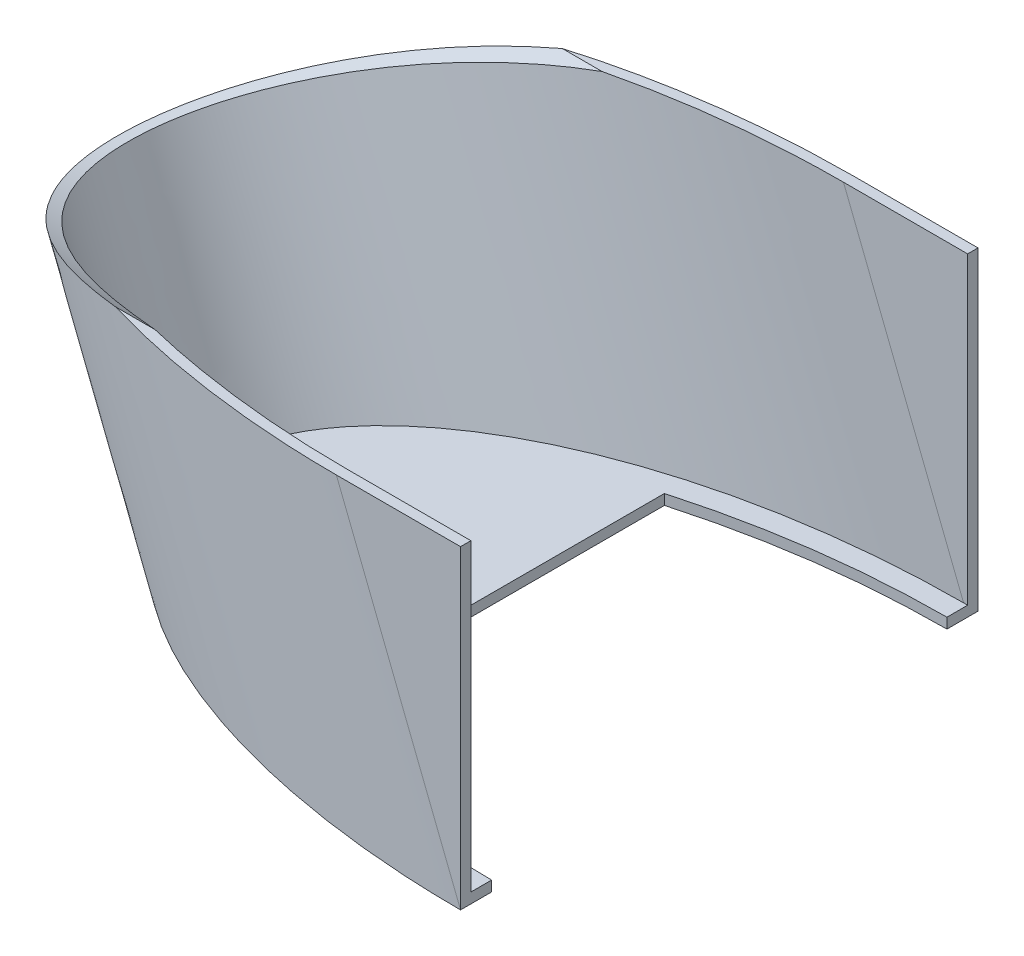
SolidWorks part; units mm, degrees
ref_plane "Front Plane" through (0, 0, 0) normal (0, 0, 1) x (1, 0, 0)
ref_plane "Top Plane" through (0, 0, 0) normal (0, 1, 0) x (1, 0, 0)
ref_plane "Right Plane" through (0, 0, 0) normal (1, 0, 0) x (0, 0, -1)
sketch "Sketch1" plane through (0, 0, 0) normal (0, 1, 0) x (1, 0, 0)
  line L1 (76.2, 38.1) -> (177.8, 38.1)
  line L3 (76.2, -38.1) -> (177.8, -38.1)
  ellipse E0 centre (76.2, 0) end of major axis (0, 0) minor radius 38.1 (76.2, 38.1) -> (76.2, -38.1) ccw
  ellipse E1 centre (177.8, 0) end of major axis (304.8, 0) minor radius 38.1 (177.8, -38.1) -> (177.8, 38.1) ccw
  point P0 (0, 0)
  dimension "D1" = 101.6
  dimension "D2" = 76.2
  dimension "D3" = 127
  dimension "D4" = 76.2
sketch "Sketch2" plane through (0, 0, 0) normal (0, 1, 0) x (1, 0, 0)
  line L0 (76.2, 39.6875) -> (76.2, 34.925)
  line L1 (76.2, -34.925) -> (76.2, -39.6875)
  line L2 (38.1, 29.6867) -> (38.1, -29.6867)
  arc A0 (76.2, 34.925) -> (38.1, 29.6867) centre (76.2, -106.2522) ccw
  arc A1 (76.2, -34.925) -> (38.1, -29.6867) centre (76.2, 106.2522) cw
  spline S0 degree 3 poles (-2756.2385, -896.1138) (489.227, -194.984) (220.9762, 50.0546) (56.8633, 33.7326) (52.1768, 33.0214) (43.1901, 31.1602) (38.8902, 30.0102) (30.8531, 27.3251) (27.1162, 25.7899) (20.3605, 22.412) (17.3423, 20.5693) (12.1462, 16.6811) (9.9697, 14.6362) (6.521, 10.4733) (5.2494, 8.3584) (3.9967, 5.2097) (3.6874, 4.1635) (3.2767, 2.0782) (3.175, 1.039) (3.175, -1.039) (3.2767, -2.0782) (3.6874, -4.1635) (3.9967, -5.2097) (5.2494, -8.3584) (6.521, -10.4733) (9.9697, -14.6362) (12.1462, -16.6811) (17.3423, -20.5693) (20.3605, -22.412) (27.1162, -25.7899) (30.8531, -27.3251) (38.8902, -30.0102) (43.1901, -31.1602) (52.1768, -33.0214) (56.8633, -33.7326) (220.9742, -50.0544) (489.2202, 194.9779) (-2756.1159, 896.0873) knots -2.018576 -2.018576 -2.018576 -2.018576 0.0625 0.0625 0.125 0.125 0.1875 0.1875 0.25 0.25 0.3125 0.3125 0.375 0.375 0.4375 0.4375 0.46875 0.46875 0.5 0.5 0.53125 0.53125 0.5625 0.5625 0.625 0.625 0.6875 0.6875 0.75 0.75 0.8125 0.8125 0.875 0.875 0.9375 0.9375 3.01855 3.01855 3.01855 3.01855 only from (76.2, 34.925) to (76.2, -34.925)
  spline S1 degree 3 poles (76.2, 34.925) (71.3166, 34.925) (66.4334, 34.6844) (56.8633, 33.7326) (52.1768, 33.0214) (43.1901, 31.1602) (38.8902, 30.0102) (30.8531, 27.3251) (27.1162, 25.7899) (20.3605, 22.412) (17.3423, 20.5693) (12.1462, 16.6811) (9.9697, 14.6362) (6.521, 10.4733) (5.2494, 8.3584) (3.9967, 5.2097) (3.6874, 4.1635) (3.2767, 2.0782) (3.175, 1.039) (3.175, -1.039) (3.2767, -2.0782) (3.6874, -4.1635) (3.9967, -5.2097) (5.2494, -8.3584) (6.521, -10.4733) (9.9697, -14.6362) (12.1462, -16.6811) (17.3423, -20.5693) (20.3605, -22.412) (27.1162, -25.7899) (30.8531, -27.3251) (38.8902, -30.0102) (43.1901, -31.1602) (52.1768, -33.0214) (56.8633, -33.7326) (66.4334, -34.6844) (71.3166, -34.925) (76.2, -34.925) knots 0 0 0 0 0.0625 0.0625 0.125 0.125 0.1875 0.1875 0.25 0.25 0.3125 0.3125 0.375 0.375 0.4375 0.4375 0.46875 0.46875 0.5 0.5 0.53125 0.53125 0.5625 0.5625 0.625 0.625 0.6875 0.6875 0.75 0.75 0.8125 0.8125 0.875 0.875 0.9375 0.9375 1 1 1 1 construction
  spline S2 degree 3 poles (-2745.7812, -914.7939) (502.7802, -205.6802) (228.1411, 55.5532) (56.2323, 38.4558) (51.3824, 37.7204) (42.0528, 35.7882) (37.5734, 34.5915) (29.1516, 31.7779) (25.2094, 30.1611) (18.0076, 26.5602) (14.7481, 24.5763) (9.0337, 20.3002) (6.5785, 18.008) (2.5772, 13.178) (1.031, 10.6388) (-1.0528, 5.4007) (-1.5875, 2.7014) (-1.5875, -2.7014) (-1.0528, -5.4007) (1.031, -10.6388) (2.5772, -13.178) (6.5785, -18.008) (9.0337, -20.3002) (14.7481, -24.5763) (18.0076, -26.5602) (25.2094, -30.1611) (29.1516, -31.7779) (37.5734, -34.5915) (42.0528, -35.7882) (51.3824, -37.7204) (56.2323, -38.4558) (228.14, -55.5531) (502.7764, 205.6765) (-2745.7129, 914.779) knots -2.047908 -2.047908 -2.047908 -2.047908 0.0625 0.0625 0.125 0.125 0.1875 0.1875 0.25 0.25 0.3125 0.3125 0.375 0.375 0.4375 0.4375 0.5 0.5 0.5625 0.5625 0.625 0.625 0.6875 0.6875 0.75 0.75 0.8125 0.8125 0.875 0.875 0.9375 0.9375 3.047893 3.047893 3.047893 3.047893 only from (76.2, 39.6875) to (76.2, -39.6875)
  spline S3 degree 3 poles (76.2, 39.6875) (71.1608, 39.6875) (66.1217, 39.4394) (56.2323, 38.4558) (51.3824, 37.7204) (42.0528, 35.7882) (37.5734, 34.5915) (29.1516, 31.7779) (25.2094, 30.1611) (18.0076, 26.5602) (14.7481, 24.5763) (9.0337, 20.3002) (6.5785, 18.008) (2.5772, 13.178) (1.031, 10.6388) (-1.0528, 5.4007) (-1.5875, 2.7014) (-1.5875, -2.7014) (-1.0528, -5.4007) (1.031, -10.6388) (2.5772, -13.178) (6.5785, -18.008) (9.0337, -20.3002) (14.7481, -24.5763) (18.0076, -26.5602) (25.2094, -30.1611) (29.1516, -31.7779) (37.5734, -34.5915) (42.0528, -35.7882) (51.3824, -37.7204) (56.2323, -38.4558) (66.1217, -39.4394) (71.1608, -39.6875) (76.2, -39.6875) knots 0 0 0 0 0.0625 0.0625 0.125 0.125 0.1875 0.1875 0.25 0.25 0.3125 0.3125 0.375 0.375 0.4375 0.4375 0.5 0.5 0.5625 0.5625 0.625 0.625 0.6875 0.6875 0.75 0.75 0.8125 0.8125 0.875 0.875 0.9375 0.9375 1 1 1 1
  dimension "D3" = 38.1
  dimension "D1" = 3.175
  dimension "D2" = 1.5875
extrude "Boss-Extrude1" add sketch "Sketch2" along normal blind 1.5875
sketch "Sketch3" plane through (0, 0, 0) normal (0, 1, 0) x (1, 0, 0)
  line L0 (76.2, 39.6875) -> (76.2, 38.1)
  line L1 (76.2, -38.1) -> (76.2, -39.6875)
  ellipse E0 centre (76.2, 0) end of major axis (152.4, 0) minor radius 38.1 (76.2, 38.1) -> (76.2, -38.1) ccw construction
  ellipse E1 centre (76.2, 0) end of major axis (152.4, 0) minor radius 38.1 (76.2, 38.1) -> (76.2, -38.1) ccw
  spline S0 degree 3 poles (-1771.3642, -690.6129) (441.885, -150.0126) (209.21, 53.6704) (56.2323, 38.4558) (51.3824, 37.7204) (42.0528, 35.7882) (37.5734, 34.5915) (29.1516, 31.7779) (25.2094, 30.1611) (18.0076, 26.5602) (14.7481, 24.5763) (9.0337, 20.3002) (6.5785, 18.008) (2.5772, 13.178) (1.031, 10.6388) (-1.0528, 5.4007) (-1.5875, 2.7014) (-1.5875, -2.7014) (-1.0528, -5.4007) (1.031, -10.6388) (2.5772, -13.178) (6.5785, -18.008) (9.0337, -20.3002) (14.7481, -24.5763) (18.0076, -26.5602) (25.2094, -30.1611) (29.1516, -31.7779) (37.5734, -34.5915) (42.0528, -35.7882) (51.3824, -37.7204) (56.2323, -38.4558) (209.208, -53.6702) (441.8786, 150.007) (-1771.2734, 690.5907) knots -1.808621 -1.808621 -1.808621 -1.808621 0.0625 0.0625 0.125 0.125 0.1875 0.1875 0.25 0.25 0.3125 0.3125 0.375 0.375 0.4375 0.4375 0.5 0.5 0.5625 0.5625 0.625 0.625 0.6875 0.6875 0.75 0.75 0.8125 0.8125 0.875 0.875 0.9375 0.9375 2.808595 2.808595 2.808595 2.808595 only from (76.2, 39.6875) to (76.2, -39.6875) construction
  spline S1 degree 3 poles (76.2, 39.6875) (71.1608, 39.6875) (66.1217, 39.4394) (56.2323, 38.4558) (51.3824, 37.7204) (42.0528, 35.7882) (37.5734, 34.5915) (29.1516, 31.7779) (25.2094, 30.1611) (18.0076, 26.5602) (14.7481, 24.5763) (9.0337, 20.3002) (6.5785, 18.008) (2.5772, 13.178) (1.031, 10.6388) (-1.0528, 5.4007) (-1.5875, 2.7014) (-1.5875, -2.7014) (-1.0528, -5.4007) (1.031, -10.6388) (2.5772, -13.178) (6.5785, -18.008) (9.0337, -20.3002) (14.7481, -24.5763) (18.0076, -26.5602) (25.2094, -30.1611) (29.1516, -31.7779) (37.5734, -34.5915) (42.0528, -35.7882) (51.3824, -37.7204) (56.2323, -38.4558) (66.1217, -39.4394) (71.1608, -39.6875) (76.2, -39.6875) knots 0 0 0 0 0.0625 0.0625 0.125 0.125 0.1875 0.1875 0.25 0.25 0.3125 0.3125 0.375 0.375 0.4375 0.4375 0.5 0.5 0.5625 0.5625 0.625 0.625 0.6875 0.6875 0.75 0.75 0.8125 0.8125 0.875 0.875 0.9375 0.9375 1 1 1 1
sketch "Sketch8" plane through (0, 0, 0) normal (0, 0, 1) x (1, 0, 0)
  line L1 (-1.5875, 0) -> (-20.6375, 48.26)
  point P2 (0, 0)
  dimension "D1" = 48.26
  dimension "D2" = 19.05
sweep "Sweep3" add profiles "Sketch3" path "Sketch8"
ref_plane "Plane2" through (0, 0, -38.1) normal (0, 0, 1) x (1, 0, 0)
sketch "Sketch14" plane through (0, 0, -38.1) normal (0, 0, 1) x (1, 0, 0)
  line L0 (57.15, 48.26) -> (76.2, 0)
  line L1 (76.2, 0) -> (76.2, 48.26)
  line L2 (76.2, 48.26) -> (57.15, 48.26)
  line L3 (76.2, 0) -> (177.8, 0) construction
  line L4 (76.2, 1.5875) -> (76.2, 0) construction
  point P4 (0, 0)
  point P6 (76.2, 0)
extrude "Boss-Extrude3" add sketch "Sketch14" against normal blind 1.5875
mirror "Mirror2" about plane through (0, 0, 0) normal (0, 0, 1) of "Boss-Extrude3"
sketch "Sketch15" plane through (0, 0, 0) normal (1, 0, 0) x (0, 0, -1)
  line L0 (38.1, 0) -> (-38.1, 0) construction
  circle A0 centre (0, 93.98) radius 57.15
  point P4 (0, 0)
  dimension "D1" = 93.98
  dimension "D2" = 114.3
extrude "Cut-Extrude1" cut sketch "Sketch15" against normal through all and the other way through all
hole_wizard "CSK for #6 Flat Head Socket Cap Screw1" positions "Sketch16" profile "Sketch17" countersink size "#6" standard "ANSI Inch" end condition through all
sketch "Sketch16" plane through (0, 0, 0) normal (0, -1, 0) x (-1, 0, 0)
  point P0 (-19.05, 0)
  point P4 (0, 0)
  dimension "D1" = 19.05
sketch "Sketch17" plane through (19.05, 0, 0) normal (1, 0, 0) x (0, 0, -1)
  line L0 (0, 0) -> (0, 54.1768)
  line L1 (0, 54.1768) -> (1.8986, 54.1768)
  line L2 (1.8986, 54.1768) -> (1.8986, 2.301)
  line L3 (1.8986, 2.301) -> (3.8989, 0)
  line L5 (3.8989, 0) -> (0, 0)
  line L6 (-1.8986, 2.301) -> (-3.8989, 0) construction
  line L11 (0, -6.35) -> (0, 107.95) construction
  dimension "Thru Hole Dia." = 3.7973
  dimension "Thru Hole Depth" = 54.1768
  dimension "Near C'Sink Dia." = 7.7978
  dimension "Near C'Sink Angle" = 82
